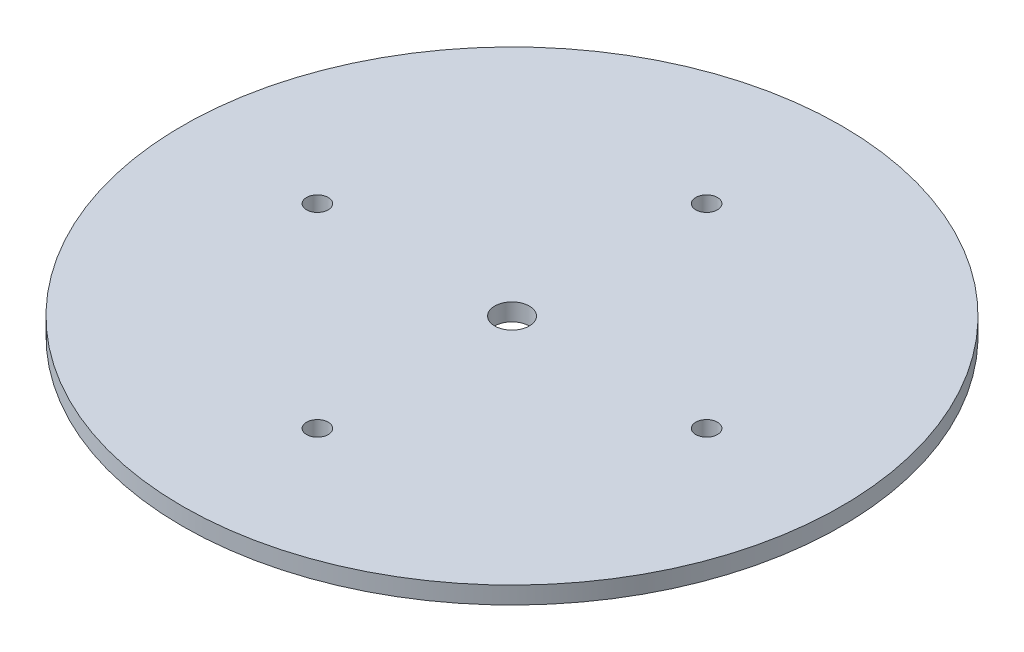
SolidWorks part; units mm, degrees
material "1060 Alloy"
ref_plane "Front Plane" through (0, 0, 0) normal (0, 0, 1) x (1, 0, 0)
ref_plane "Top Plane" through (0, 0, 0) normal (0, 1, 0) x (1, 0, 0)
ref_plane "Right Plane" through (0, 0, 0) normal (1, 0, 0) x (0, 0, -1)
sketch "Sketch1" plane through (0, 0, 0) normal (0, 1, 0) x (1, 0, 0)
  line L0 (45, 0) -> (-45, 0) construction
  line L1 (0, -45) -> (0, 0) construction
  circle A0 centre (0, 0) radius 76.2
  circle A1 centre (-45, 0) radius 2.5
  circle A2 centre (45, 0) radius 2.5
  circle A3 centre (0, 0) radius 4
  circle A4 centre (0, -45) radius 2.5
  circle A5 centre (0, 45) radius 2.5
  point P6 (0, 0)
  dimension "D1" = 152.4
  dimension "D2" = 5
  dimension "D3" = 5
  dimension "D5" = 8
  dimension "D6" = 5
  dimension "D4" = 90
  dimension "D7" = 45
extrude "Boss-Extrude1" add sketch "Sketch1" along normal blind 4
